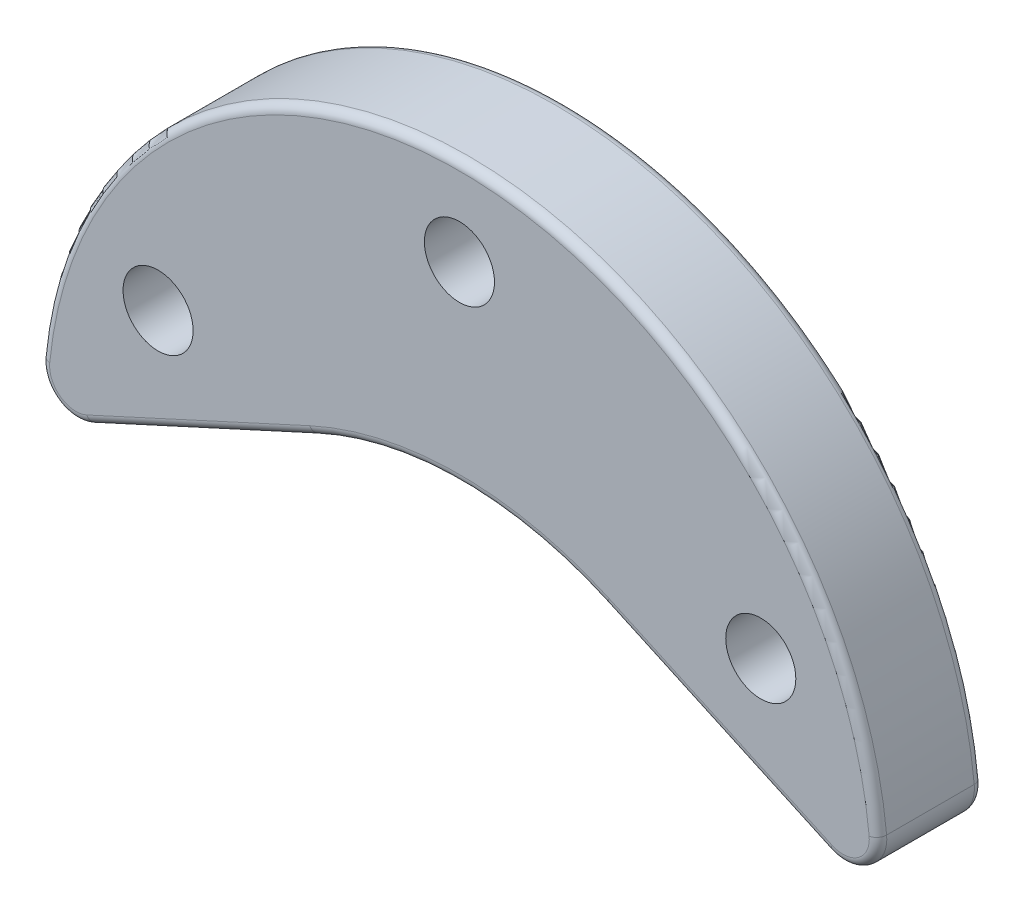
SolidWorks part; units mm, degrees
material "Free-Cutting Brass, UNS C36000"
ref_plane "Front Plane" through (0, 0, 0) normal (0, 0, 1) x (1, 0, 0)
ref_plane "Top Plane" through (0, 0, 0) normal (0, 1, 0) x (1, 0, 0)
ref_plane "Right Plane" through (0, 0, 0) normal (1, 0, 0) x (0, 0, -1)
ref_plane "Plane1" through (0, 0, -6) normal (0, 0, 1) x (1, 0, 0)
sketch "Sketch3" plane through (0, 0, -6) normal (0, 0, 1) x (1, 0, 0)
  line L0 (4.166, 3.0909) -> (11.9898, -0.4944)
  line L1 (-4.166, 3.0909) -> (-11.9898, -0.4944)
  arc A0 (11.9898, -0.4944) -> (-11.9898, -0.4944) centre (0, 0) ccw
  arc A1 (4.166, 3.0909) -> (-4.166, 3.0909) centre (0, -6) ccw
  dimension "D3" = 6
extrude "Boss-Extrude2" add sketch "Sketch3" along normal blind 3 separate body
fillet "Fillet2" radius 1 2 edges at (-11.9898, -0.4944, -4.5) (11.9898, -0.4944, -4.5)
fillet "Fillet3" radius 0.25 12 edges at (-11.5274, 0.2697, -6) (-11.5274, 0.2697, -3) (11.5274, 0.2697, -3) (11.5274, 0.2697, -6) (7.3479, 1.6328, -3) (7.3479, 1.6328, -6) (-7.3479, 1.6328, -3) (-7.3479, 1.6328, -6) (0, 4, -3) (0, 4, -6) (0, 12, -6) (0, 12, -3)
sketch "Sketch4" plane through (0, 0, -6) normal (0, 0, -1) x (-1, 0, 0)
  circle A0 centre (0, 9.5) radius 1
  circle A1 centre (8.6, 4) radius 1
  circle A2 centre (-8.6, 4) radius 1
  dimension "D1" = 2
  dimension "D2" = 8.6
  dimension "D3" = 8.6
  dimension "D4" = 9.5
  dimension "D5" = 4
extrude "Cut-Extrude1" cut sketch "Sketch4" against normal blind 10
